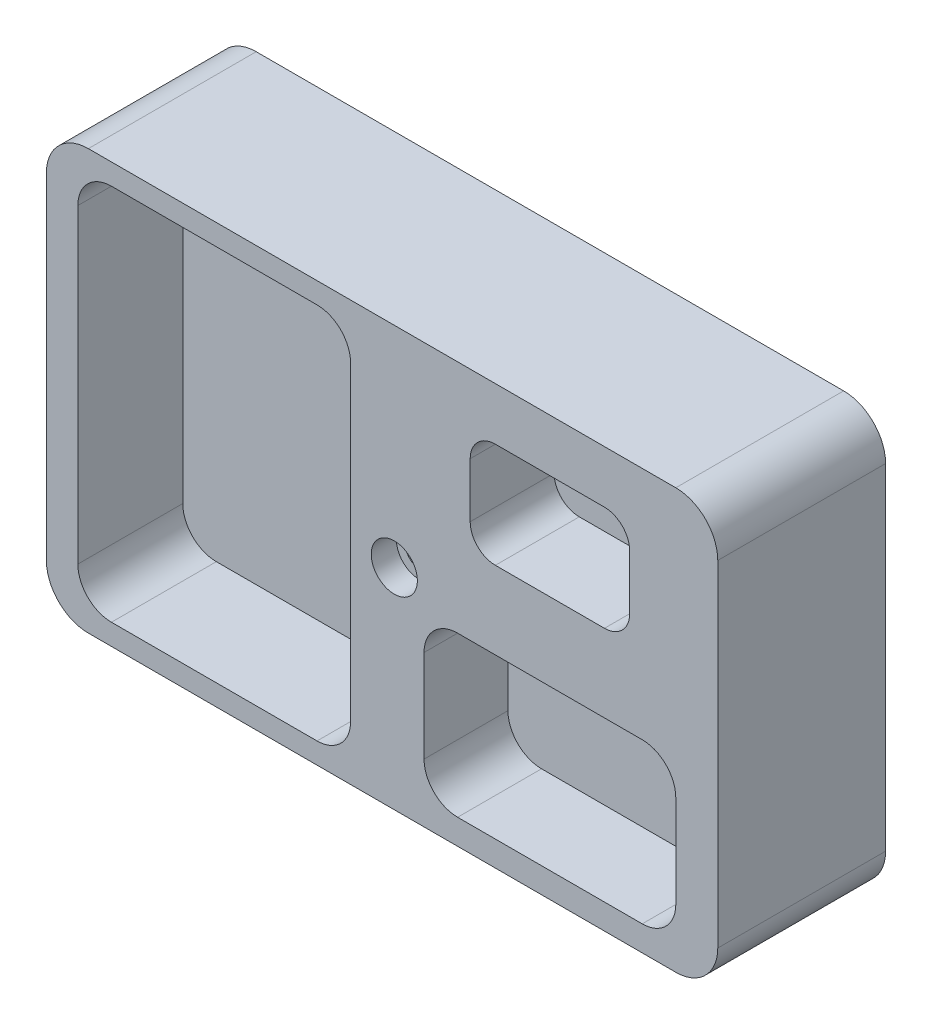
SolidWorks part; units mm, degrees
ref_plane "Front Plane" through (0, 0, 0) normal (0, 0, 1) x (1, 0, 0)
ref_plane "Top Plane" through (0, 0, 0) normal (0, 1, 0) x (1, 0, 0)
ref_plane "Right Plane" through (0, 0, 0) normal (1, 0, 0) x (0, 0, -1)
sketch "Sketch1" plane through (0, 0, 0) normal (0, 0, 1) x (1, 0, 0)
  line L1 (-80, 50) -> (80, 50)
  line L2 (-80, 50) -> (-80, -50)
  line L3 (-80, -50) -> (80, -50)
  line L4 (80, 50) -> (80, -50)
  line L5 (-80, 50) -> (80, -50) construction
  line L6 (-80, -50) -> (80, 50) construction
  point P0 (0, 0)
  dimension "D1" = 160
  dimension "D2" = 100
extrude "Boss-Extrude1" add sketch "Sketch1" against normal blind 40
sketch "Sketch2" plane through (0, 0, 0) normal (0, 0, 1) x (1, 0, 0)
  line L0 (0, 0) -> (-80, 0) construction
  line L1 (-72.5, -45) -> (-7.5, -45)
  line L2 (-72.5, -45) -> (-72.5, 45)
  line L3 (-72.5, 45) -> (-7.5, 45)
  line L4 (-7.5, -45) -> (-7.5, 45)
  line L5 (-72.5, -45) -> (-7.5, 45) construction
  line L6 (-72.5, 45) -> (-7.5, -45) construction
  line L7 (-80, 50) -> (-80, -50) construction
  point P0 (0, 0)
  point P10 (-40, 0)
  point P11 (-40, 0)
  dimension "D1" = 65
  dimension "D2" = 90
extrude "Cut-Extrude1" cut sketch "Sketch2" against normal blind 25
fillet "Fillet1" radius 8 4 edges at (-7.5, -45, -12.5) (-72.5, -45, -12.5) (-72.5, 45, -12.5) (-7.5, 45, -12.5)
sketch "Sketch3" plane through (0, 0, 0) normal (0, 0, 1) x (1, 0, 0)
  line L0 (0, 50) -> (0, -50) construction
  line L1 (80, 50) -> (-80, 50) construction
  line L2 (-80, -50) -> (80, -50) construction
  line L3 (0, 0) -> (80, 0) construction
  line L4 (80, -50) -> (80, 50) construction
  line L5 (40, 0) -> (40, 50) construction
  line L6 (10, -44) -> (70, -44)
  line L7 (10, -44) -> (10, -6)
  line L8 (10, -6) -> (70, -6)
  line L9 (70, -44) -> (70, -6)
  line L10 (10, -44) -> (70, -6) construction
  line L11 (10, -6) -> (70, -44) construction
  line L12 (21, 12.5) -> (59, 12.5)
  line L13 (21, 12.5) -> (21, 37.5)
  line L14 (21, 37.5) -> (59, 37.5)
  line L15 (59, 12.5) -> (59, 37.5)
  line L16 (21, 12.5) -> (59, 37.5) construction
  line L17 (21, 37.5) -> (59, 12.5) construction
  line L18 (40, 25) -> (80, 25) construction
  line L19 (40, 0) -> (40, -50) construction
  line L20 (40, -25) -> (80, -25) construction
  point P11 (40, -25)
  point P18 (40, 25)
  dimension "D1" = 38
  dimension "D2" = 25
  dimension "D3" = 60
  dimension "D4" = 38
extrude "Cut-Extrude2" cut sketch "Sketch3" against normal blind 20
fillet "Fillet2" radius 6 4 edges at (59, 12.5, -10) (21, 12.5, -10) (59, 37.5, -10) (21, 37.5, -10)
fillet "Fillet3" radius 8 4 edges at (10, -44, -10) (70, -44, -10) (70, -6, -10) (10, -6, -10)
fillet "Fillet4" radius 10 4 edges at (-80, 50, -20) (80, 50, -20) (80, -50, -20) (-80, -50, -20)
hole_wizard "CBORE for M6 SHCS1" positions "Sketch6" profile "Sketch5" counterbore size "M6" standard "ANSI Metric" end condition through all
sketch "Sketch6" plane through (0, 0, 0) normal (0, 0, 1) x (1, 0, 0)
  point P0 (2.9103, 0)
sketch "Sketch5" plane through (2.9103, 0, 0) normal (1, 0, 0) x (0, -1, 0)
  line L0 (0, 0) -> (0, 40)
  line L1 (0, 40) -> (3.3, 40)
  line L3 (3.3, 40) -> (3.3, 6)
  line L4 (3.3, 6) -> (5.5, 6)
  line L5 (5.5, 6) -> (5.5, 0)
  line L7 (5.5, 0) -> (0, 0)
  line L11 (0, -6.35) -> (0, 107.95) construction
  dimension "Thru Hole Dia." = 6.6
  dimension "Thru Hole Depth" = 40
  dimension "C'Bore Dia." = 11
  dimension "C'Bore Depth" = 6
